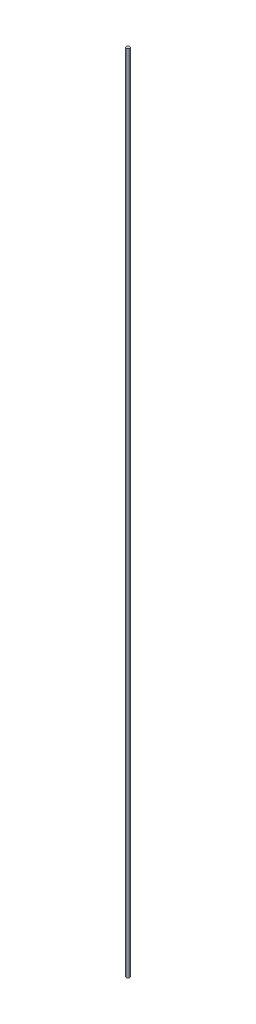
SolidWorks part; units mm, degrees
material "Thornel Mat VMA"
ref_plane "Front Plane" through (0, 0, 0) normal (0, 0, 1) x (1, 0, 0)
ref_plane "Top Plane" through (0, 0, 0) normal (0, 1, 0) x (1, 0, 0)
ref_plane "Right Plane" through (0, 0, 0) normal (1, 0, 0) x (0, 0, -1)
sketch "Sketch1" plane through (0, 0, 0) normal (0, 1, 0) x (1, 0, 0)
  circle A0 centre (0, 0) radius 0.75
  dimension "D1" = 1.5
extrude "Boss-Extrude1" add sketch "Sketch1" along normal mid plane 360
